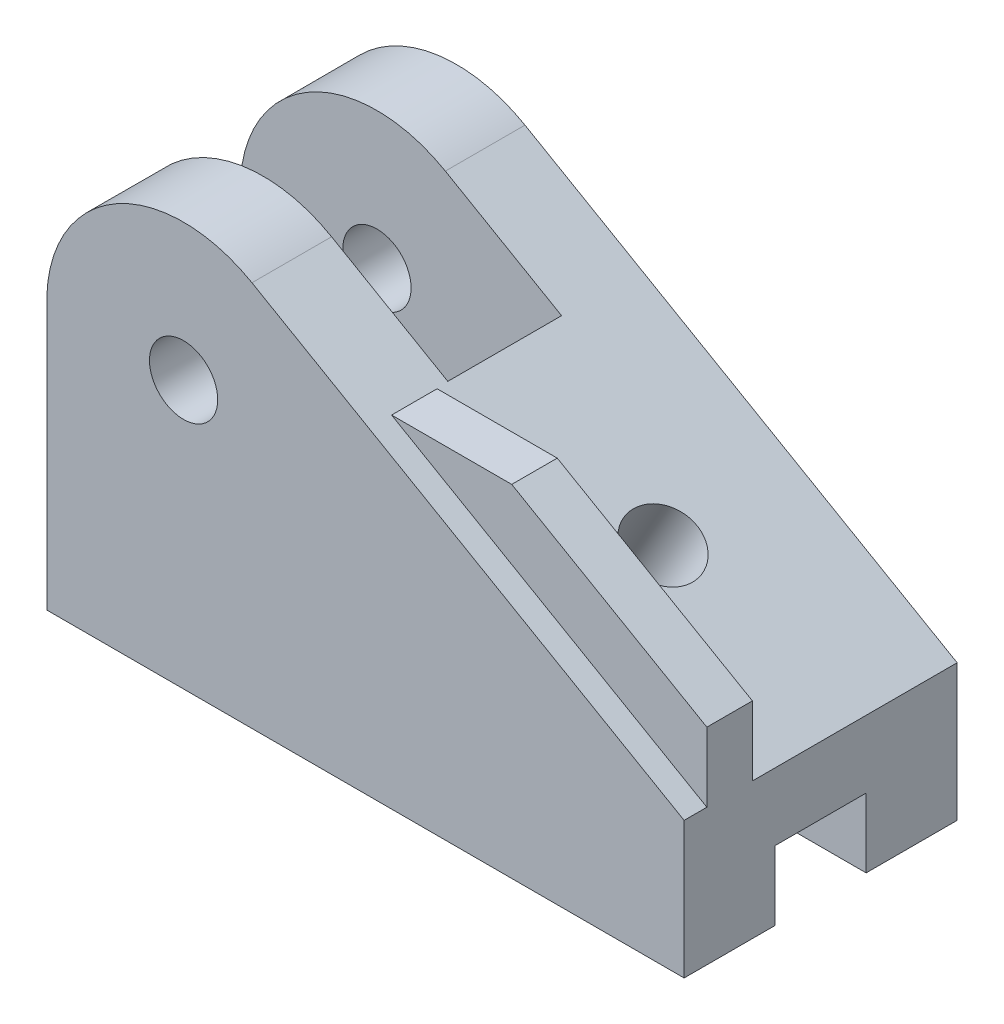
SolidWorks part; units mm, degrees
material "Nylon 101"
ref_plane "Front Plane" through (0, 0, 0) normal (0, 0, 1) x (1, 0, 0)
ref_plane "Top Plane" through (0, 0, 0) normal (0, 1, 0) x (1, 0, 0)
ref_plane "Right Plane" through (0, 0, 0) normal (1, 0, 0) x (0, 0, -1)
sketch "Sketch1" plane through (0, 0, 0) normal (0, 0, 1) x (1, 0, 0)
  line L0 (0, 0) -> (88.9, 0)
  line L1 (0, 0) -> (0, 37.338)
  line L2 (88.9, 0) -> (88.9, 19.05)
  line L3 (0, 37.338) -> (19.05, 37.338) construction
  line L4 (88.9, 19.05) -> (28.5936, 53.8679)
  arc A2 (28.5936, 53.8679) -> (0, 36.1481) centre (19.05, 37.338) ccw
  dimension "D4" = 19.05
  dimension "D1" = 88.9
  dimension "D2" = 37.338
  dimension "D3" = 19.05
  dimension "D5" = 30
extrude "Boss-Extrude1" add sketch "Sketch1" along normal mid plane 38.1
sketch "Sketch2" plane through (88.9, 0, 0) normal (1, 0, 0) x (0, 0, -1)
  line L0 (0, 0) -> (0, 9.652) construction
  line L1 (6.35, 0) -> (6.35, 9.652)
  line L2 (-6.35, 0) -> (-6.35, 9.652)
  line L3 (6.35, 9.652) -> (-6.35, 9.652)
  line L4 (-6.35, 0) -> (6.35, 0)
  line L5 (19.05, 0) -> (19.05, 19.05) construction
  dimension "D3" = 12.7
  dimension "D1" = 9.652
  dimension "D2" = 12.7
extrude "Cut-Extrude1" cut sketch "Sketch2" against normal through all
ref_plane "Plane1" through (0, 0, 12.7) normal (0, 0, 1) x (1, 0, 0)
sketch "Sketch3" plane through (0, 0, 12.7) normal (0, 0, 1) x (1, 0, 0)
  line L0 (88.9, 28.7287) -> (61.6699, 44.45)
  line L1 (88.9, 19.05) -> (88.9, 28.7287)
  line L2 (88.9, 19.05) -> (44.9059, 44.45)
  line L5 (93.091, 26.309) -> (47.3136, 52.7386) construction
  line L6 (61.6699, 44.45) -> (44.9059, 44.45)
  line L7 (88.9, 19.05) -> (43.1226, 45.4796) construction
  dimension "D1" = 8.382
  dimension "D2" = 25.4
  dimension "D3" = 44.9059
extrude "Boss-Extrude2" add sketch "Sketch3" along normal mid plane 6.35
ref_plane "Plane7" through (0, 0, 0) normal (0, 0, 1) x (1, 0, 0)
sketch "Sketch17" plane through (0, 0, 0) normal (0, 0, 1) x (1, 0, 0)
  line L0 (0, 25.4) -> (33.782, 25.4)
  line L1 (0, 0) -> (0, 36.1481) construction
  line L2 (0, 0) -> (88.9, 0) construction
  line L5 (0, 25.4) -> (0, 56.8322)
  line L6 (0, 56.8322) -> (51.9294, 56.8322)
  line L7 (33.782, 25.4) -> (51.9294, 56.8322)
  dimension "D1" = 25.4
  dimension "D2" = 33.782
  dimension "D3" = 120
  dimension "D4" = 51.9294
extrude "Cut-Extrude12" cut sketch "Sketch17" against normal mid plane 15.875
hole_wizard "1/2 (0.375) Diameter Hole1" positions "Sketch18" profile "Sketch19" hole size "1/2" standard "ANSI Inch" end condition through all
sketch "Sketch18" plane through (30.4739, 52.7823, 0) normal (0.5, 0.866, 0) x (0.866, -0.5, 0)
  line L0 (67.4647, -9.525) -> (67.4647, 19.05) construction
  line L1 (67.4647, 19.05) -> (-2.1712, 19.05) construction
  point P0 (42.0647, 0)
  point P5 (67.4647, 4.7625)
  dimension "D1" = 25.4
  dimension "D2" = 19.05
sketch "Sketch19" plane through (66.903, 31.75, 0) normal (0, 0, 1) x (-0.866, 0.5, 0)
  line L0 (0, 0) -> (0, 60.9663)
  line L1 (0, 60.9663) -> (4.7625, 60.9663)
  line L2 (4.7625, 60.9663) -> (4.7625, 0)
  line L5 (4.7625, 0) -> (0, 0)
  line L11 (0, -6.35) -> (0, 107.95) construction
  dimension "Thru Hole Dia." = 9.525
  dimension "Thru Hole Depth" = 60.9663
hole_wizard "1/2 (0.375) Diameter Hole2" positions "Sketch20" profile "Sketch21" hole size "1/2" standard "ANSI Inch" end condition through all
sketch "Sketch20" plane through (0, 0, 19.05) normal (0, 0, 1) x (1, 0, 0)
  point P0 (19.05, 37.338)
sketch "Sketch21" plane through (19.05, 37.338, 19.05) normal (1, 0, 0) x (0, -1, 0)
  line L0 (0, 0) -> (0, 38.1)
  line L1 (0, 38.1) -> (4.7625, 38.1)
  line L2 (4.7625, 38.1) -> (4.7625, 0)
  line L5 (4.7625, 0) -> (0, 0)
  line L11 (0, -6.35) -> (0, 107.95) construction
  dimension "Thru Hole Dia." = 9.525
  dimension "Thru Hole Depth" = 38.1
